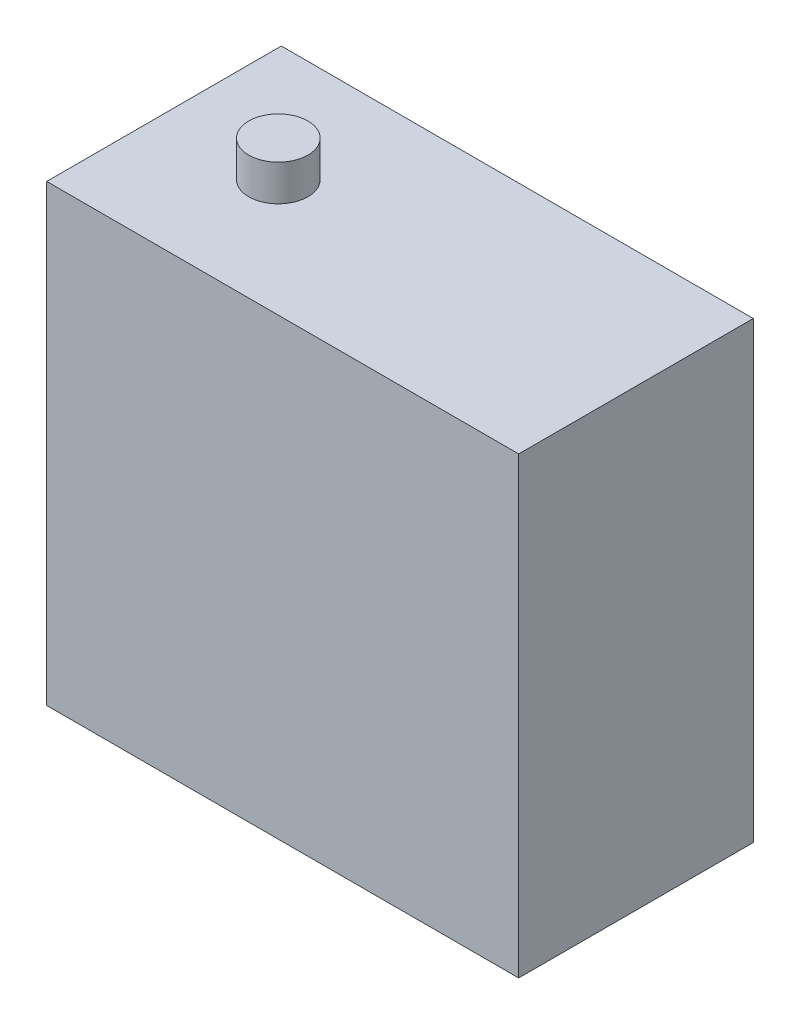
SolidWorks part; units mm, degrees
ref_plane "Front Plane" through (0, 0, 0) normal (0, 0, 1) x (1, 0, 0)
ref_plane "Top Plane" through (0, 0, 0) normal (0, 1, 0) x (1, 0, 0)
ref_plane "Right Plane" through (0, 0, 0) normal (1, 0, 0) x (0, 0, -1)
sketch "Sketch1" plane through (0, 0, 0) normal (0, 1, 0) x (1, 0, 0)
  line L1 (0, 0) -> (39.88, 0)
  line L2 (0, 0) -> (0, 19.82)
  line L3 (0, 19.82) -> (39.88, 19.82)
  line L4 (39.88, 0) -> (39.88, 19.82)
  dimension "D1" = 39.88
  dimension "D2" = 19.82
extrude "Boss-Extrude1" add sketch "Sketch1" along normal blind 38.35
sketch "Sketch2" plane through (0, 38.35, 0) normal (0, 1, 0) x (1, 0, 0)
  line L0 (0, 19.82) -> (0, 0) construction
  circle A0 centre (9.66, 9.91) radius 2.5
  dimension "D1" = 5
  dimension "D2" = 9.66
extrude "Boss-Extrude2" add sketch "Sketch2" along normal blind 3.05
